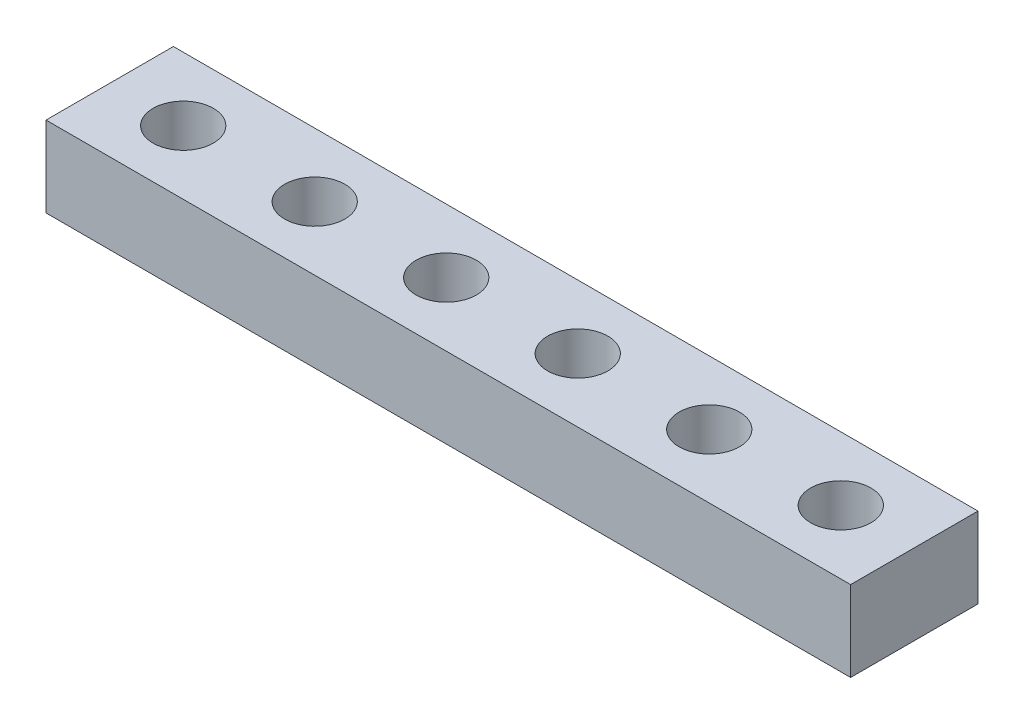
SolidWorks part; units mm, degrees
ref_plane "Front Plane" through (0, 0, 0) normal (0, 0, 1) x (1, 0, 0)
ref_plane "Top Plane" through (0, 0, 0) normal (0, 1, 0) x (1, 0, 0)
ref_plane "Right Plane" through (0, 0, 0) normal (1, 0, 0) x (0, 0, -1)
sketch "Sketch1" plane through (0, 0, 0) normal (0, 1, 0) x (1, 0, 0)
  line L0 (0, -2.375) -> (30, -2.375) construction
  line L1 (0, 0) -> (30, 0)
  line L2 (0, 0) -> (0, -4.75)
  line L3 (0, -4.75) -> (30, -4.75)
  line L4 (30, 0) -> (30, -4.75)
  line L5 (2.7409, -4.75) -> (2.7409, 0) construction
  line L6 (15, 0) -> (15, -4.75) construction
  circle A0 centre (2.7409, -2.375) radius 1.125
  circle A1 centre (7.6445, -2.375) radius 1.125
  circle A2 centre (12.5482, -2.375) radius 1.125
  circle A3 centre (17.4518, -2.375) radius 1.125
  circle A4 centre (22.3555, -2.375) radius 1.125
  circle A5 centre (27.2591, -2.375) radius 1.125
  point P13 (2.7409, -2.375)
  point P24 (15, 0)
  point P25 (0, 0)
  point P26 (2.7409, -4.75)
  dimension "D4" = 2.25
  dimension "D1" = 4.75
  dimension "D2" = 30
  dimension "D3" = 6
extrude "Boss-Extrude1" add sketch "Sketch1" along normal blind 3
